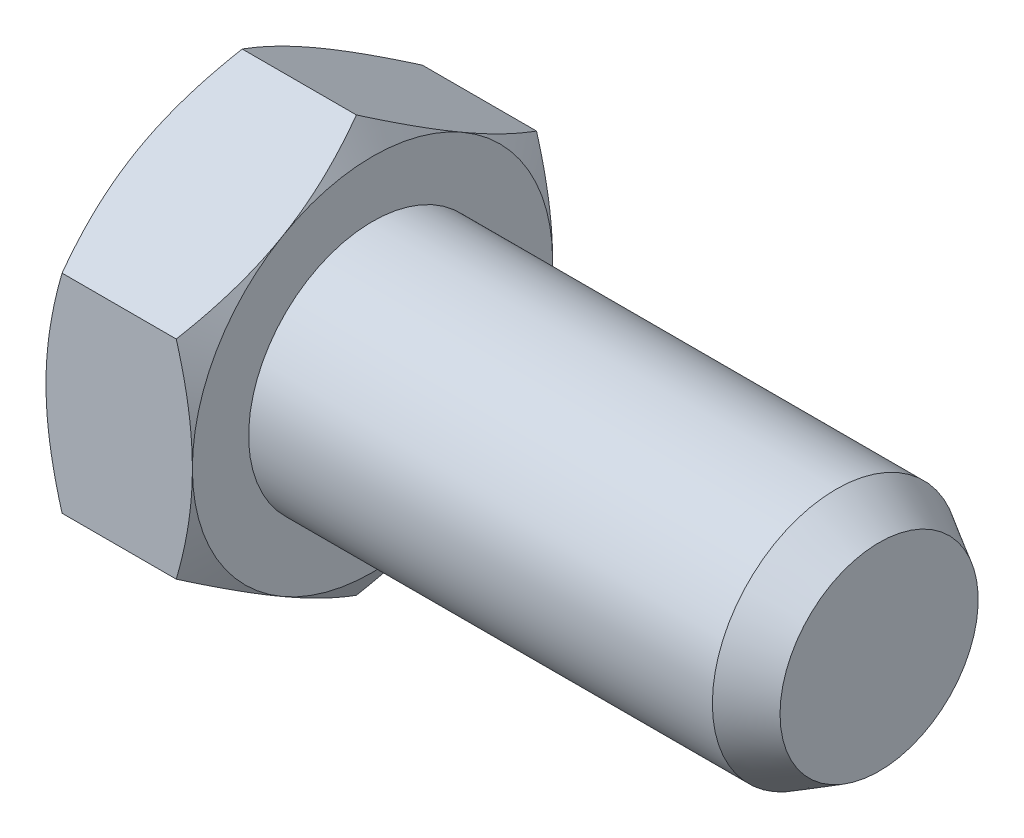
SolidWorks part; units mm, degrees
ref_plane "Front" through (0, 0, 0) normal (0, 0, 1) x (1, 0, 0)
ref_plane "Top" through (0, 0, 0) normal (0, 1, 0) x (1, 0, 0)
ref_plane "Right" through (0, 0, 0) normal (1, 0, 0) x (0, 0, -1)
sketch "Sketch1" plane through (0, 0, 0) normal (0, 0, 1) x (1, 0, 0)
  line L0 (0, 0) -> (0, 1.4)
  line L1 (0, 1.4) -> (1.3, 1.4)
  line L2 (1.3, 1.4) -> (1.3, 1.1)
  line L4 (1.3, 1.1) -> (5.8, 1.1)
  line L5 (5.8, 1.1) -> (5.8, 0)
  line L6 (5.8, 0) -> (0, 0)
  line L7 (13.1079, 0) -> (-2.2203, 0) construction
  dimension "da" = 2.8
  dimension "d" = 2.2
  dimension "k" = 1.3
  dimension "l" = 4.5
revolve "Revolve1" add sketch "Sketch1" angle 360 about L7
cosmetic thread "ThreadCosmetic" [suppressed] parameters "D2"=1.5
sketch "Sketch2" plane through (0, 0, 0) normal (-1, 0, 0) x (0, 0, 1)
  line L1 (1.6, -0.9238) -> (1.6, 0.9238)
  line L2 (1.6, 0.9238) -> (0, 1.8475)
  line L3 (0, 1.8475) -> (-1.6, 0.9238)
  line L4 (-1.6, 0.9238) -> (-1.6, -0.9238)
  line L5 (-1.6, -0.9238) -> (0, -1.8475)
  line L6 (0, -1.8475) -> (1.6, -0.9238)
  circle A0 centre (0, 0) radius 1.6 construction
  dimension "s" = 3.2
extrude "Extrude1" add sketch "Sketch2" against normal blind 1.3
sketch "Sketch3" plane through (0, 0, 0) normal (0, 1, 0) x (1, 0, 0)
  line L0 (-0.9238, 0) -> (0.65, 2.7258)
  line L1 (0.65, 2.7258) -> (1.3, 1.6)
  line L2 (0, 0) -> (-2.2444, 0) construction
  line L4 (1.3, 1.6) -> (1.3, 3.2258)
  line L5 (1.3, 3.2258) -> (-1.0238, 3.2258)
  line L6 (-0.9238, 0) -> (-1.0238, 0)
  line L7 (-1.0238, 0) -> (-1.0238, 3.2258)
  dimension "D1" = 60
  dimension "D2" = 0.5
  dimension "D3" = 0.1
  dimension "D4" = 60
revolve "Cut-Revolve2" cut sketch "Sketch3" angle 360 about L2
sketch "Sketch4" plane through (0, 0, 0) normal (0, 0, 1) x (1, 0, 0)
  line L0 (0, 0) -> (1.9538, 0) construction
  line L1 (-0.2, 0) -> (-0.2, 1.28)
  line L2 (-0.2, 1.28) -> (0.4, 1.28)
  line L3 (0.4, 1.28) -> (0.4, 0)
  line L4 (1.3, 1.4) -> (1.3, 1.1) construction
  line L5 (1.3, 1.4) -> (1.3, 1.8049) construction
  line L6 (0.4, 0) -> (-0.2, 0)
  dimension "D1" = 0.2
  dimension "k'" = 0.9
  dimension "D2" = 2.56
revolve "Cut-Revolve3" cut sketch "Sketch4" angle 360 about L0
chamfer "Chamfer1" distance 0.22 angle 60 1 edges at (5.8, 0, -1.1)
sketch "Sketch6" plane through (0, 0, 0) normal (0, 0, 1) x (1, 0, 0)
  line L0 (1.627, 0.75) -> (1.5502, 0.75)
  line L1 (1.5502, 0.75) -> (1.3481, 1.1)
  line L2 (1.627, 0.75) -> (1.829, 1.1)
  line L3 (1.3481, 1.1) -> (1.3481, 1.35)
  line L4 (1.829, 1.1) -> (1.829, 1.35)
  line L5 (1.3481, 1.35) -> (1.829, 1.35)
  line L6 (1.5886, 0.75) -> (1.5886, 0) construction
  line L7 (0, 0) -> (7.3035, 0) construction
  dimension "D2" = 60
  dimension "D3" = 0.25
  dimension "advance" = 0.4809
  dimension "minordia" = 1.5
  dimension "threadstart" = 1.5886
  dimension "D1" = 2.2
revolve "ThreadSchematic" [suppressed] cut sketch "Sketch6" angle 360 about L7
pattern_linear "ThdSchPat" [suppressed] count 10 spacing 0.4809 along (-1, 0, 0)
sketch "Sketch5" plane through (0, 0, 0) normal (0, 0, 1) x (1, 0, 0)
  line L0 (5.8, -0.88) -> (5.8, 0.88) construction
  line L2 (5.8, -1.1) -> (5.8, 0) construction
  line L3 (3.8, -1.1) -> (4.3, -1.1) construction
  line L4 (0, 0) -> (6.648, 0) construction
  line L5 (5.8, 0) -> (4.3, -1.1)
  line L6 (5.8, 0) -> (6, 0)
  line L7 (6, 0) -> (6, -1.3)
  line L8 (6, -1.3) -> (4.3, -1.3)
  line L9 (4.3, -1.3) -> (4.3, -1.1)
  line L10 (4.3, -1.1) -> (5.8, -1.1) construction
  dimension "D1" = 0.2
  dimension "y" = 2
  dimension "D2" = 0.5
  dimension "D3" = 0.2
  dimension "D4" = 2.2
revolve "EndCone" [suppressed] cut sketch "Sketch5" angle 360 about L4
equation "\"minordia@Sketch6\" = \"D2@ThreadCosmetic\""
equation "\"D1@Extrude1\" = \"k@Sketch1\""
equation "\"D2@Sketch4\" = \"s@Sketch2\" * 4 / 5"
equation "\"D1@Chamfer1\" = \"d@Sketch1\" / 10"
equation "\"D2@Sketch5\" = \"y@Sketch5\" / 4"
equation "\"threadstart@Sketch6\" = \"D1@Extrude1\"+(\"advance@Sketch6\"*0.6)"
equation "\"D1@ThdSchPat\" = int((\"l@Sketch1\"/\"advance@Sketch6\") + 0.999)"
equation "\"D3@ThdSchPat\" = \"advance@Sketch6\""
equation "\"D1@Sketch6\" = \"d@Sketch1\""
equation "\"D4@Sketch5\" = \"d@Sketch1\""
